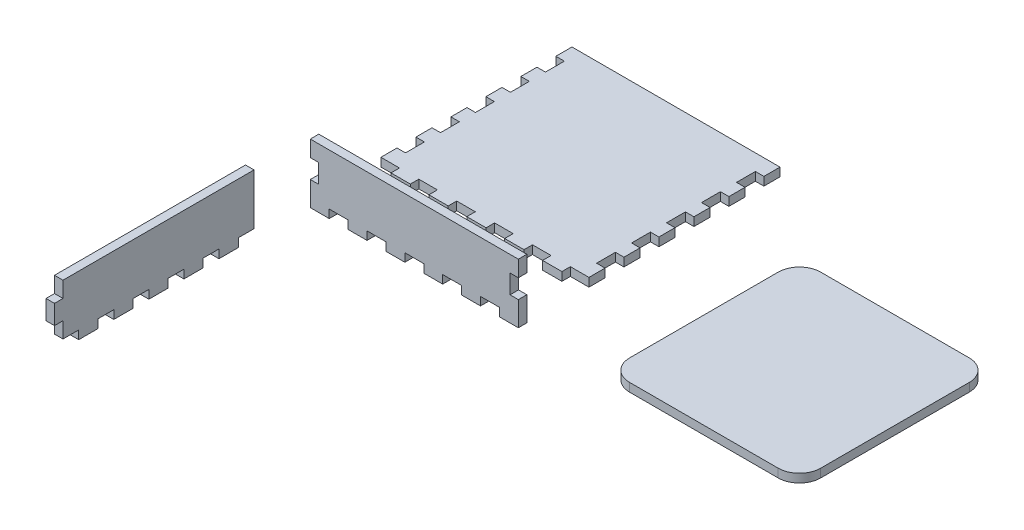
SolidWorks part; units mm, degrees
ref_plane "Front Plane" through (0, 0, 0) normal (0, 0, 1) x (1, 0, 0)
ref_plane "Top Plane" through (0, 0, 0) normal (0, 1, 0) x (1, 0, 0)
ref_plane "Right Plane" through (0, 0, 0) normal (1, 0, 0) x (0, 0, -1)
sketch "Sketch1" plane through (0, 0, 0) normal (0, 1, 0) x (1, 0, 0)
  line L1 (10, 0) -> (80, 0)
  line L2 (0, 10) -> (0, 80)
  line L3 (10, 90) -> (80, 90)
  line L4 (90, 10) -> (90, 80)
  arc A0 (0, 10) -> (10, 0) centre (10, 10) ccw
  arc A1 (90, 10) -> (80, 0) centre (80, 10) cw
  arc A2 (90, 80) -> (80, 90) centre (80, 80) ccw
  arc A3 (10, 90) -> (0, 80) centre (10, 80) ccw
  point P7 (0, 0)
  point P10 (90, 0)
  point P13 (90, 90)
  point P16 (0, 90)
  dimension "D2" = 10
  dimension "D1" = 90
  dimension "size" = 90
extrude "Boss-Extrude1" add sketch "Sketch1" along normal blind 4
sketch "Sketch2" plane through (0, 0, 0) normal (0, 0, 1) x (1, 0, 0)
  line L0 (-131.5092, 3.9665) -> (-140.4259, 3.9665) construction
  line L1 (-140.4259, 0.0665) -> (-131.5092, 0.0665)
  line L2 (-140.4259, 0.0665) -> (-140.4259, 11.5665)
  line L3 (-140.4259, 28.0665) -> (-42.4259, 28.0665)
  line L4 (-140.4259, 20.4665) -> (-140.4259, 28.0665)
  line L5 (-51.3426, 0.0665) -> (-42.4259, 0.0665)
  line L6 (-95.8759, 0.0665) -> (-95.8759, 3.9665)
  line L7 (-95.8759, 3.9665) -> (-86.9759, 3.9665)
  line L8 (-86.9759, 0.0665) -> (-86.9759, 3.9665)
  line L9 (-69.1592, 0.0665) -> (-60.2426, 0.0665)
  line L10 (-78.0592, 0.0665) -> (-78.0592, 3.9665)
  line L11 (-78.0592, 3.9665) -> (-69.1592, 3.9665)
  line L12 (-69.1592, 0.0665) -> (-69.1592, 3.9665)
  line L13 (-86.9759, 0.0665) -> (-78.0592, 0.0665)
  line L14 (-60.2426, 0.0665) -> (-60.2426, 3.9665)
  line L15 (-60.2426, 3.9665) -> (-51.3426, 3.9665)
  line L16 (-51.3426, 0.0665) -> (-51.3426, 3.9665)
  line L17 (-104.7926, 0.0665) -> (-95.8759, 0.0665)
  line L18 (-113.6926, 0.0665) -> (-113.6926, 3.9665)
  line L19 (-113.6926, 3.9665) -> (-104.7926, 3.9665)
  line L20 (-104.7926, 0.0665) -> (-104.7926, 3.9665)
  line L21 (-42.4259, 0.0665) -> (-42.4259, 11.5665)
  line L22 (-131.5092, 0.0665) -> (-131.5092, 3.9665)
  line L23 (-131.5092, 3.9665) -> (-122.6092, 3.9665)
  line L24 (-122.6092, 0.0665) -> (-122.6092, 3.9665)
  line L25 (-122.6092, 3.9665) -> (-113.6926, 3.9665) construction
  line L26 (-104.7926, 3.9665) -> (-95.8759, 3.9665) construction
  line L27 (-42.4259, 20.4665) -> (-46.3259, 20.4665)
  line L28 (-86.9759, 3.9665) -> (-78.0592, 3.9665) construction
  line L29 (-69.1592, 3.9665) -> (-60.2426, 3.9665) construction
  line L30 (-51.3426, 3.9665) -> (-42.4259, 3.9665) construction
  line L31 (-122.6092, 0.0665) -> (-113.6926, 0.0665)
  line L32 (-140.4259, 20.4665) -> (-136.5259, 20.4665)
  line L33 (-42.4259, 11.5665) -> (-46.3259, 11.5665)
  line L34 (-46.3259, 20.4665) -> (-46.3259, 11.5665)
  line L35 (-46.3259, 20.4665) -> (-46.3259, 28.0665) construction
  line L36 (-46.3259, 11.5665) -> (-46.3259, 3.9665) construction
  line L37 (-42.4259, 20.4665) -> (-42.4259, 28.0665)
  line L39 (-140.4259, 11.5665) -> (-136.5259, 11.5665)
  line L40 (-136.5259, 20.4665) -> (-136.5259, 11.5665)
  dimension "D1" = 28
  dimension "D2" = 98
  dimension "D3" = 8.9
  dimension "D4" = 3.9
extrude "Boss-Extrude2" add sketch "Sketch2" against normal blind 4 separate body
sketch "Sketch4" plane through (0, 0, 0) normal (0, 1, 0) x (1, 0, 0)
  line L0 (-42.4259, 4) -> (-42.4259, 0) construction
  line L1 (-51.1759, 29.2654) -> (-60.2759, 29.2654)
  line L2 (-42.4259, 33.2654) -> (-42.4259, 40.8487)
  line L3 (-42.4259, 123.2654) -> (-140.4259, 123.2654)
  line L4 (-140.4259, 33.2654) -> (-140.4259, 40.8487)
  line L5 (-46.4259, 40.8487) -> (-46.4259, 33.2654) construction
  line L6 (-131.6759, 29.2654) -> (-122.5759, 29.2654)
  line L7 (-131.6759, 29.2654) -> (-131.6759, 33.2654)
  line L8 (-69.0259, 29.2654) -> (-78.1259, 29.2654)
  line L9 (-122.5759, 29.2654) -> (-122.5759, 33.2654)
  line L10 (-113.8259, 29.2654) -> (-104.7259, 29.2654)
  line L11 (-113.8259, 29.2654) -> (-113.8259, 33.2654)
  line L12 (-86.8759, 29.2654) -> (-95.9759, 29.2654)
  line L13 (-104.7259, 29.2654) -> (-104.7259, 33.2654)
  line L14 (-95.9759, 29.2654) -> (-86.8759, 29.2654)
  line L15 (-95.9759, 29.2654) -> (-95.9759, 33.2654)
  line L16 (-104.7259, 29.2654) -> (-113.8259, 29.2654)
  line L17 (-86.8759, 29.2654) -> (-86.8759, 33.2654)
  line L18 (-78.1259, 29.2654) -> (-69.0259, 29.2654)
  line L19 (-78.1259, 29.2654) -> (-78.1259, 33.2654)
  line L20 (-122.5759, 29.2654) -> (-131.6759, 29.2654)
  line L21 (-69.0259, 29.2654) -> (-69.0259, 33.2654)
  line L22 (-60.2759, 29.2654) -> (-51.1759, 29.2654)
  line L23 (-60.2759, 29.2654) -> (-60.2759, 33.2654)
  line L24 (-42.4259, 49.7487) -> (-42.4259, 57.332)
  line L25 (-51.1759, 29.2654) -> (-51.1759, 33.2654)
  line L26 (-42.4259, 33.2654) -> (-51.1759, 33.2654)
  line L27 (-42.4259, 40.8487) -> (-46.4259, 40.8487)
  line L28 (-60.2759, 33.2654) -> (-69.0259, 33.2654)
  line L29 (-78.1259, 33.2654) -> (-86.8759, 33.2654)
  line L30 (-95.9759, 33.2654) -> (-104.7259, 33.2654)
  line L32 (-113.8259, 33.2654) -> (-122.5759, 33.2654)
  line L33 (-131.6759, 33.2654) -> (-140.4259, 33.2654)
  line L34 (-42.4259, 66.232) -> (-42.4259, 73.8154)
  line L35 (-42.4259, 49.7487) -> (-46.4259, 49.7487)
  line L36 (-46.4259, 40.8487) -> (-46.4259, 49.7487)
  line L37 (-42.4259, 57.332) -> (-46.4259, 57.332)
  line L38 (-42.4259, 82.7154) -> (-42.4259, 90.2987)
  line L39 (-42.4259, 66.232) -> (-46.4259, 66.232)
  line L40 (-46.4259, 57.332) -> (-46.4259, 66.232)
  line L41 (-42.4259, 73.8154) -> (-46.4259, 73.8154)
  line L42 (-42.4259, 99.1987) -> (-42.4259, 106.782)
  line L43 (-42.4259, 82.7154) -> (-46.4259, 82.7154)
  line L44 (-46.4259, 73.8154) -> (-46.4259, 82.7154)
  line L45 (-42.4259, 90.2987) -> (-46.4259, 90.2987)
  line L46 (-42.4259, 115.682) -> (-42.4259, 123.2654)
  line L47 (-42.4259, 99.1987) -> (-46.4259, 99.1987)
  line L48 (-46.4259, 90.2987) -> (-46.4259, 99.1987)
  line L49 (-42.4259, 106.782) -> (-46.4259, 106.782)
  line L50 (-140.4259, 115.682) -> (-140.4259, 123.2654)
  line L51 (-42.4259, 115.682) -> (-46.4259, 115.682)
  line L52 (-46.4259, 106.782) -> (-46.4259, 115.682)
  line L53 (-46.4259, 49.7487) -> (-46.4259, 57.332) construction
  line L54 (-46.4259, 66.232) -> (-46.4259, 73.8154) construction
  line L55 (-46.4259, 82.7154) -> (-46.4259, 90.2987) construction
  line L56 (-46.4259, 99.1987) -> (-46.4259, 106.782) construction
  line L57 (-46.4259, 115.682) -> (-46.4259, 123.2654) construction
  line L58 (-140.4259, 40.8487) -> (-136.4259, 40.8487)
  line L60 (-140.4259, 49.7487) -> (-136.4259, 49.7487)
  line L61 (-136.4259, 40.8487) -> (-136.4259, 49.7487)
  line L62 (-140.4259, 57.332) -> (-136.4259, 57.332)
  line L63 (-140.4259, 49.7487) -> (-140.4259, 57.332)
  line L64 (-140.4259, 66.232) -> (-136.4259, 66.232)
  line L65 (-136.4259, 57.332) -> (-136.4259, 66.232)
  line L66 (-140.4259, 73.8154) -> (-136.4259, 73.8154)
  line L67 (-140.4259, 66.232) -> (-140.4259, 73.8154)
  line L68 (-140.4259, 82.7154) -> (-136.4259, 82.7154)
  line L69 (-136.4259, 73.8154) -> (-136.4259, 82.7154)
  line L70 (-140.4259, 90.2987) -> (-136.4259, 90.2987)
  line L71 (-140.4259, 82.7154) -> (-140.4259, 90.2987)
  line L72 (-140.4259, 99.1987) -> (-136.4259, 99.1987)
  line L73 (-136.4259, 90.2987) -> (-136.4259, 99.1987)
  line L74 (-140.4259, 106.782) -> (-136.4259, 106.782)
  line L75 (-140.4259, 99.1987) -> (-140.4259, 106.782)
  line L76 (-140.4259, 115.682) -> (-136.4259, 115.682)
  line L77 (-136.4259, 106.782) -> (-136.4259, 115.682)
  dimension "D1" = 98
  dimension "D2" = 94
  dimension "D3" = 9.1
  dimension "D4" = 8.9
extrude "Boss-Extrude3" add sketch "Sketch4" along normal blind 4 separate body contours L77 L74 L75 L72 L73 L70 L71 L68 L69 L66 L67 L64 L65 L62 L63 L60 L61 L58 L4 L33 L7 L6 L9 L32 L11 L10 L13 L30 L15 L12 L17 L29 L19 L8 L21 L28 L23 L1 L25 L26 L2 L27 L36 L35 L24 L37 L40 L39 L34 L41 L44
sketch "Sketch5" plane through (-140.4259, 0, 0) normal (-1, 0, 0) x (0, 0, 1)
  line L0 (33.9245, 4.7413) -> (26.5078, 4.7413)
  line L1 (33.9245, 0.7413) -> (43.0245, 0.7413)
  line L2 (26.5078, 4.7413) -> (26.5078, 28.7413)
  line L3 (26.5078, 28.7413) -> (116.5078, 28.7413)
  line L4 (120.5078, 12.1913) -> (120.5078, 21.2913)
  line L5 (33.9245, 0.7413) -> (43.0245, 0.7413)
  line L6 (33.9245, 0.7413) -> (33.9245, 4.7413)
  line L7 (116.5078, 12.1913) -> (116.5078, 4.7413)
  line L8 (43.0245, 0.7413) -> (43.0245, 4.7413)
  line L9 (50.4411, 0.7413) -> (59.5411, 0.7413)
  line L10 (50.4411, 0.7413) -> (50.4411, 4.7413)
  line L11 (120.5078, 21.2913) -> (116.5078, 21.2913)
  line L12 (59.5411, 0.7413) -> (59.5411, 4.7413)
  line L13 (66.9578, 0.7413) -> (76.0578, 0.7413)
  line L14 (66.9578, 0.7413) -> (66.9578, 4.7413)
  line L15 (120.5078, 21.2913) -> (120.5078, 12.1913)
  line L16 (76.0578, 0.7413) -> (76.0578, 4.7413)
  line L17 (83.4745, 0.7413) -> (92.5745, 0.7413)
  line L18 (83.4745, 0.7413) -> (83.4745, 4.7413)
  line L19 (120.5078, 12.1913) -> (116.5078, 12.1913)
  line L20 (92.5745, 0.7413) -> (92.5745, 4.7413)
  line L21 (99.9911, 0.7413) -> (109.0911, 0.7413)
  line L22 (99.9911, 0.7413) -> (99.9911, 4.7413)
  line L24 (109.0911, 0.7413) -> (109.0911, 4.7413)
  line L25 (43.0245, 4.7413) -> (50.4411, 4.7413)
  line L26 (59.5411, 4.7413) -> (66.9578, 4.7413)
  line L27 (76.0578, 4.7413) -> (83.4745, 4.7413)
  line L28 (92.5745, 4.7413) -> (99.9911, 4.7413)
  line L29 (109.0911, 4.7413) -> (116.5078, 4.7413)
  line L30 (50.4411, 0.7413) -> (59.5411, 0.7413)
  line L31 (66.9578, 0.7413) -> (76.0578, 0.7413)
  line L32 (83.4745, 0.7413) -> (92.5745, 0.7413)
  line L33 (99.9911, 0.7413) -> (109.0911, 0.7413)
  line L34 (116.5078, 21.2913) -> (116.5078, 28.7413)
  dimension "D1" = 28
  dimension "D2" = 94
  dimension "D3" = 9.1
extrude "Boss-Extrude4" add sketch "Sketch5" along normal blind 4 separate body contours L11 L34 L3 L2 L0 L6 L1 L8 L25 L10 L9 L12 L26 L14 L13 L16 L27 L18 L17 L20 L28 L22 L21 L24 L29 L7 L19 L4
other "Save Bodies1"
equation "\"size\"= 90"
equation "\"D1@Sketch1\" = \"size\""
equation "\"mat_thick\"= 4"
equation "\"num_coasters\"= 6"
equation "\"D1@Sketch2\" = \"num_coasters\"*\"mat_thick\"+\"mat_thick\""
equation "\"D2@Sketch2\" = \"size\"+2*\"mat_thick\""
equation "\"kerf\"= 0.1"
equation "\"D3@Sketch2\" = \"size\"/10-\"kerf\""
equation "\"D4@Sketch2\" = \"mat_thick\"-\"kerf\""
equation "\"D1@Boss-Extrude2\" = \"mat_thick\""
equation "\"D1@Sketch4\" = \"size\"+2*\"mat_thick\""
equation "\"D2@Sketch4\" = \"size\"+\"mat_thick\""
equation "\"D3@Sketch4\" = \"size\"/10+\"kerf\""
equation "\"D4@Sketch4\" = \"size\"/10-\"kerf\""
equation "\"D1@Sketch5\" = \"mat_thick\"*(\"num_coasters\"+1)"
equation "\"D2@Sketch5\" = \"size\"+\"mat_thick\""
equation "\"D3@Sketch5\" = \"size\"/10+\"kerf\""
